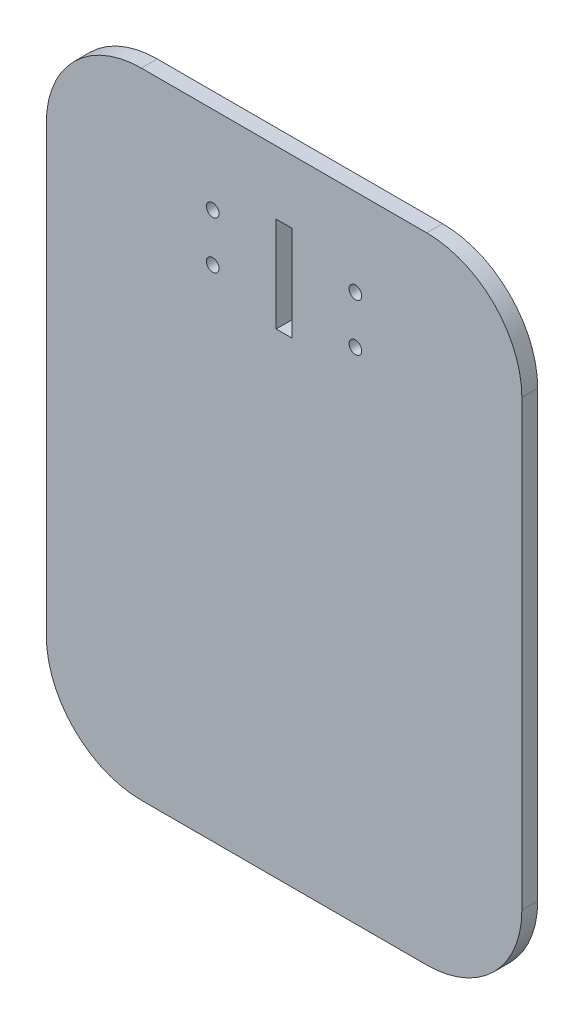
SolidWorks part; units mm, degrees
ref_plane "Alzado" through (0, 0, 0) normal (0, 0, 1) x (1, 0, 0)
ref_plane "Planta" through (0, 0, 0) normal (0, 1, 0) x (1, 0, 0)
ref_plane "Vista lateral" through (0, 0, 0) normal (1, 0, 0) x (0, 0, -1)
sketch "Croquis1" plane through (0, 0, 0) normal (0, 0, 1) x (1, 0, 0)
  line L1 (-242.2955, 139.278) -> (-92.2955, 139.278)
  line L2 (-242.2955, 139.278) -> (-242.2955, -60.722)
  line L3 (-242.2955, -60.722) -> (-92.2955, -60.722)
  line L4 (-92.2955, 139.278) -> (-92.2955, -60.722)
  line L5 (-169.7955, 119.278) -> (-164.7955, 119.278)
  line L6 (-169.7955, 119.278) -> (-169.7955, 89.278)
  line L7 (-169.7955, 89.278) -> (-164.7955, 89.278)
  line L8 (-164.7955, 119.278) -> (-164.7955, 89.278)
  point P8 (-167.2955, 119.278)
  point P9 (-167.2955, 139.278)
  dimension "D1" = 200
  dimension "D2" = 150
  dimension "D3" = 5
  dimension "D4" = 30
  dimension "D5" = 20
extrude "Saliente-Extruir1" add sketch "Croquis1" along normal blind 5
fillet "Redondeo1" radius 30 4 edges at (-92.2955, -60.722, 2.5) (-242.2955, -60.722, 2.5) (-92.2955, 139.278, 2.5) (-242.2955, 139.278, 2.5)
sketch "Croquis2" plane through (0, 0, 5) normal (0, 0, 1) x (1, 0, 0)
  line L0 (-164.7955, 89.278) -> (-164.7955, 119.278) construction
  line L1 (-167.2955, 119.278) -> (-167.2955, 89.278) construction
  line L2 (-164.7955, 119.278) -> (-169.7955, 119.278) construction
  line L3 (-169.7955, 89.278) -> (-164.7955, 89.278) construction
  line L4 (-169.7955, 104.278) -> (-164.7955, 104.278) construction
  line L5 (-169.7955, 119.278) -> (-169.7955, 89.278) construction
  circle A0 centre (-144.7955, 111.778) radius 2
  circle A1 centre (-189.7955, 111.778) radius 2
  circle A2 centre (-189.7955, 96.778) radius 2
  circle A3 centre (-144.7955, 96.778) radius 2
  dimension "D1" = 20
  dimension "D2" = 4
  dimension "D3" = 7.5
extrude "Cortar-Extruir1" cut sketch "Croquis2" against normal up to next
